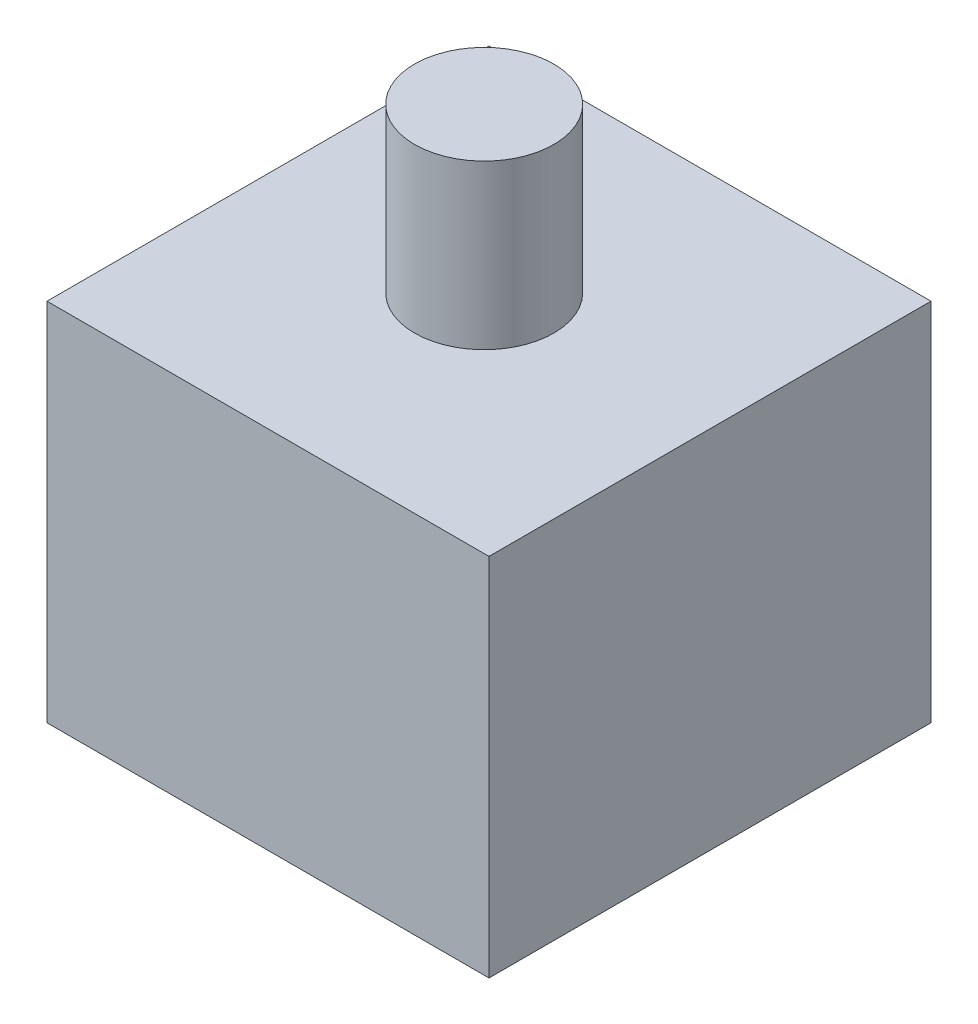
SolidWorks part; units mm, degrees
ref_plane "Plan de face" through (0, 0, 0) normal (0, 0, 1) x (1, 0, 0)
ref_plane "Plan de dessus" through (0, 0, 0) normal (0, 1, 0) x (1, 0, 0)
ref_plane "Plan de droite" through (0, 0, 0) normal (1, 0, 0) x (0, 0, -1)
sketch "Esquisse1" plane through (0, 0, 0) normal (0, 1, 0) x (1, 0, 0)
  line L1 (-77.4333, 27.0633) -> (-31.4333, 27.0633)
  line L2 (-77.4333, 27.0633) -> (-77.4333, -18.9367)
  line L3 (-77.4333, -18.9367) -> (-31.4333, -18.9367)
  line L4 (-31.4333, 27.0633) -> (-31.4333, -18.9367)
  line L5 (-77.4333, 27.0633) -> (-31.4333, -18.9367) construction
  line L6 (-77.4333, -18.9367) -> (-31.4333, 27.0633) construction
  dimension "D1" = 46
  dimension "D2" = 46
extrude "Boss.-Extru.1" add sketch "Esquisse1" along normal blind 38
sketch "Esquisse2" plane through (0, 38, 0) normal (0, 1, 0) x (1, 0, 0)
  line L0 (-77.4333, -18.9367) -> (-31.4333, -18.9367) construction
  line L1 (-31.4333, -18.9367) -> (-31.4333, 27.0633) construction
  circle A0 centre (-55.4333, 4.5633) radius 7.25
  dimension "D1" = 14.5
  dimension "D2" = 23.5
  dimension "D3" = 24
extrude "Boss.-Extru.2" add sketch "Esquisse2" along normal blind 17
